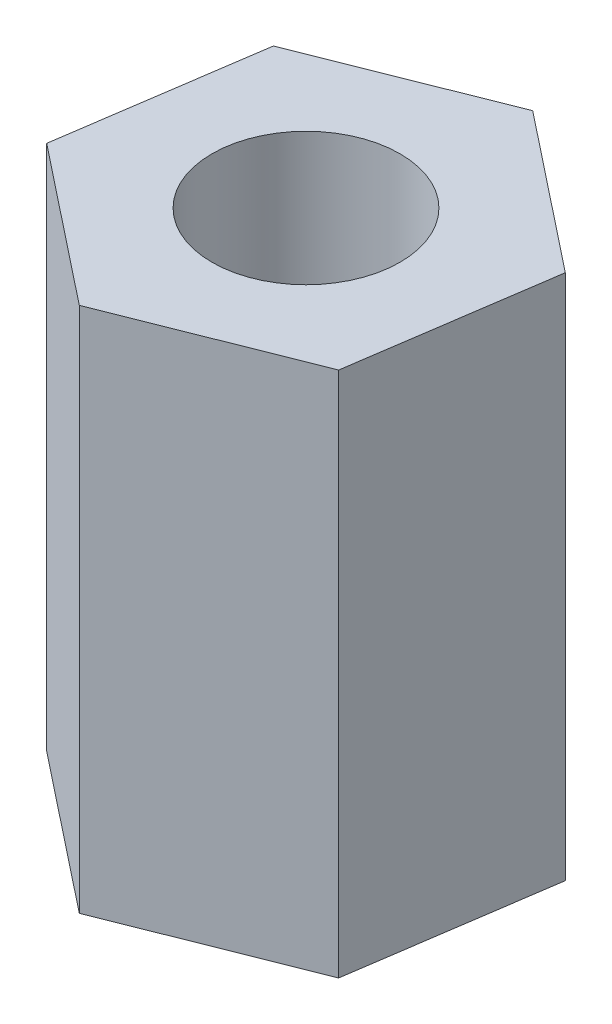
SolidWorks part; units mm, degrees
ref_plane "Alzado" through (0, 0, 0) normal (0, 0, 1) x (1, 0, 0)
ref_plane "Planta" through (0, 0, 0) normal (0, 1, 0) x (1, 0, 0)
ref_plane "Vista lateral" through (0, 0, 0) normal (1, 0, 0) x (0, 0, -1)
sketch "Croquis base" plane through (0, 0, 0) normal (0, 1, 0) x (1, 0, 0)
  line L1 (2.0823, -1.6485) -> (2.4688, 0.9791)
  line L2 (2.4688, 0.9791) -> (0.3865, 2.6275)
  line L3 (0.3865, 2.6275) -> (-2.0823, 1.6485)
  line L4 (-2.0823, 1.6485) -> (-2.4688, -0.9791)
  line L5 (-2.4688, -0.9791) -> (-0.3865, -2.6275)
  line L6 (-0.3865, -2.6275) -> (2.0823, -1.6485)
  circle A0 centre (0, 0) radius 2.3 construction
extrude "Saliente-Extruir1" add sketch "Croquis base" along normal blind 7
sketch "Croquis cara" plane through (0, 7, 0) normal (0, 1, 0) x (1, 0, 0)
  circle A0 centre (0, 0) radius 1.25
  dimension "D1" = 2.5
extrude "Cortar-Extruir1" cut sketch "Croquis cara" against normal blind 7
